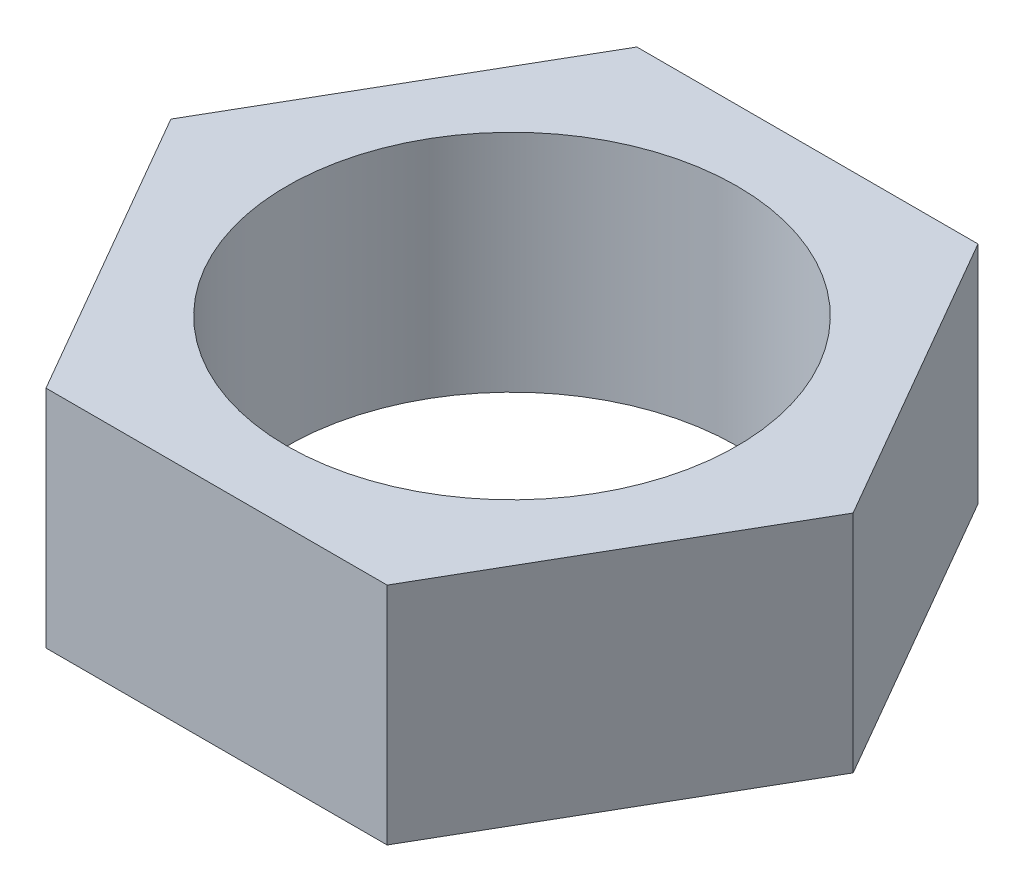
SolidWorks part; units mm, degrees
ref_plane "Front Plane" through (0, 0, 0) normal (0, 0, 1) x (1, 0, 0)
ref_plane "Top Plane" through (0, 0, 0) normal (0, 1, 0) x (1, 0, 0)
ref_plane "Right Plane" through (0, 0, 0) normal (1, 0, 0) x (0, 0, -1)
sketch "Sketch1" plane through (0, 0, 0) normal (0, 1, 0) x (1, 0, 0)
  line L1 (19.2474, 0) -> (9.6237, 16.6688)
  line L2 (9.6237, 16.6688) -> (-9.6237, 16.6687)
  line L3 (-9.6237, 16.6687) -> (-19.2474, 0)
  line L4 (-19.2474, 0) -> (-9.6237, -16.6688)
  line L5 (-9.6237, -16.6688) -> (9.6237, -16.6687)
  line L6 (9.6237, -16.6687) -> (19.2474, 0)
  circle A0 centre (0, 0) radius 16.6688 construction
  circle A1 centre (0, 0) radius 12.7
  dimension "D1" = 33.3375
  dimension "D2" = 16.6687
extrude "Boss-Extrude1" add sketch "Sketch1" along normal blind 12.7
